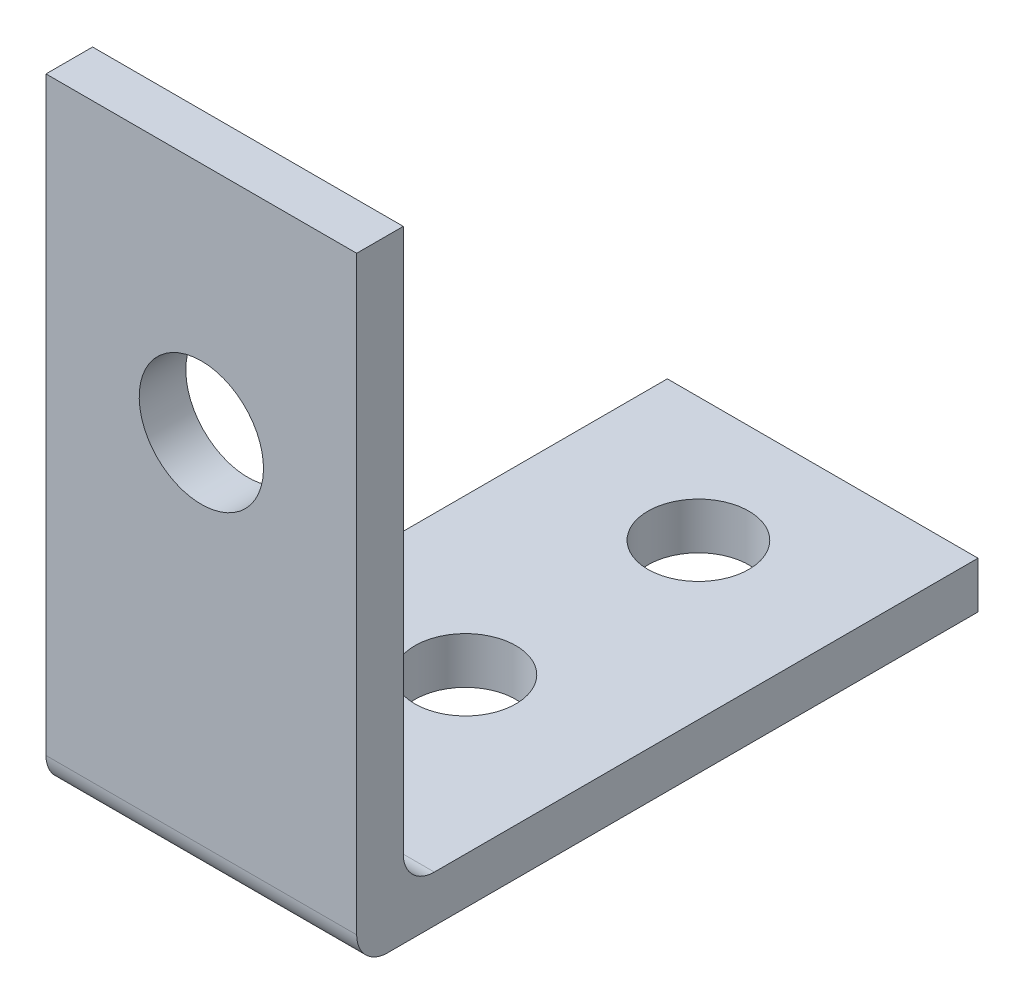
SolidWorks part; units mm, degrees
ref_plane "Front Plane" through (0, 0, 0) normal (0, 0, 1) x (1, 0, 0)
ref_plane "Top Plane" through (0, 0, 0) normal (0, 1, 0) x (1, 0, 0)
ref_plane "Right Plane" through (0, 0, 0) normal (1, 0, 0) x (0, 0, -1)
sketch "Sketch1" plane through (0, 0, 0) normal (1, 0, 0) x (0, 0, -1)
  line L0 (0, 2) -> (0, 40)
  line L1 (0, 40) -> (3, 40)
  line L2 (3, 40) -> (3, 5)
  line L3 (5, 3) -> (40, 3)
  line L4 (40, 3) -> (40, 0)
  line L5 (40, 0) -> (2, 0)
  arc A0 (2, 0) -> (0, 2) centre (2, 2) cw
  arc A1 (5, 3) -> (3, 5) centre (5, 5) cw
  point P9 (0, 0)
  dimension "D5" = 2
  dimension "D6" = 2
  dimension "D1" = 3
  dimension "D2" = 40
  dimension "D3" = 40
  dimension "D4" = 3
extrude "Boss-Extrude1" add sketch "Sketch1" along normal blind 20
sketch "Sketch3" plane through (0, 0, -3) normal (0, 0, -1) x (-1, 0, 0)
  line L0 (-20, 0) -> (0, 0) construction
  line L1 (0, 5) -> (0, 40) construction
  circle A0 centre (-10, 25) radius 4
  dimension "D1" = 25
  dimension "D2" = 10
extrude "Cut-Extrude1" cut sketch "Sketch3" against normal through all
sketch "Sketch4" plane through (0, 3, 0) normal (0, 1, 0) x (1, 0, 0)
  line L0 (20, 40) -> (0, 40) construction
  line L1 (20, 40) -> (20, 5) construction
  circle A0 centre (10, 32) radius 3.25
  circle A1 centre (10, 17) radius 3.25
  dimension "D1" = 8
  dimension "D2" = 10
  dimension "D3" = 10
  dimension "D4" = 15
extrude "Cut-Extrude2" cut sketch "Sketch4" against normal through all
